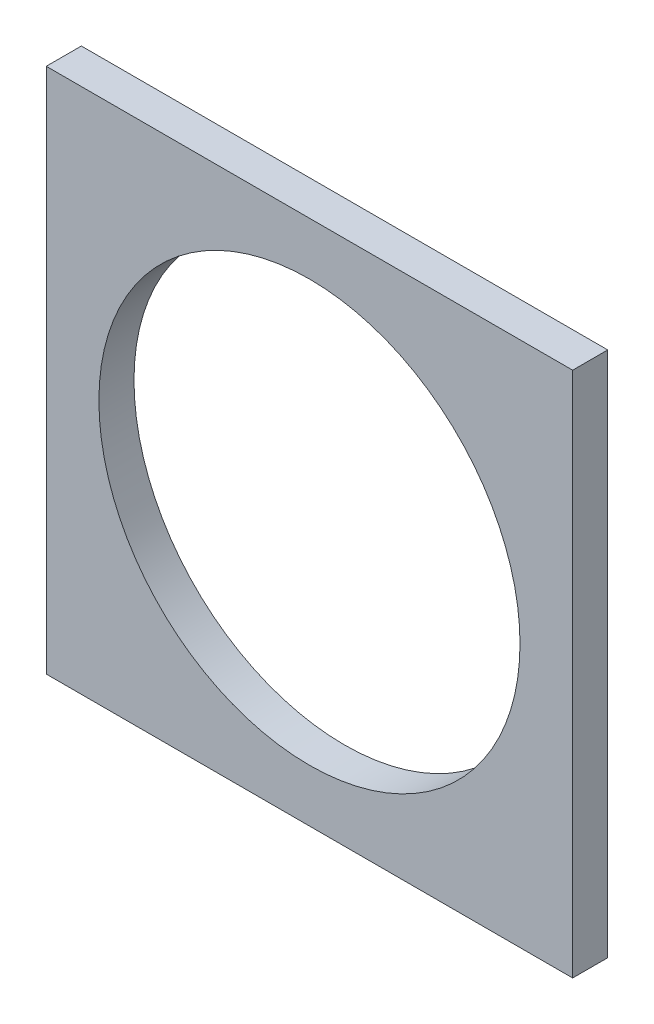
SolidWorks part; units mm, degrees
ref_plane "Front Plane" through (0, 0, 0) normal (0, 0, 1) x (1, 0, 0)
ref_plane "Top Plane" through (0, 0, 0) normal (0, 1, 0) x (1, 0, 0)
ref_plane "Right Plane" through (0, 0, 0) normal (1, 0, 0) x (0, 0, -1)
sketch "Sketch1" plane through (0, 0, 0) normal (0, 0, 1) x (1, 0, 0)
  line L1 (-15, 15) -> (15, 15)
  line L2 (-15, 15) -> (-15, -15)
  line L3 (-15, -15) -> (15, -15)
  line L4 (15, 15) -> (15, -15)
  line L5 (-15, 15) -> (15, -15) construction
  line L6 (-15, -15) -> (15, 15) construction
  circle A0 centre (0, 0) radius 12
  point P0 (0, 0)
  dimension "D1" = 30
  dimension "D2" = 30
extrude "Boss-Extrude1" add sketch "Sketch1" along normal blind 2
